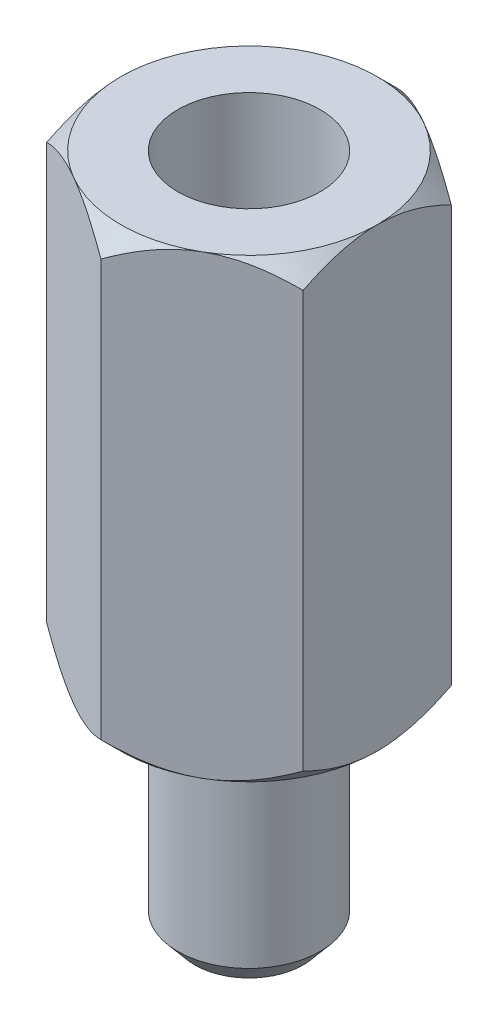
SolidWorks part; units mm, degrees
ref_plane "Front Plane" through (0, 0, 0) normal (0, 0, 1) x (1, 0, 0)
ref_plane "Top Plane" through (0, 0, 0) normal (0, 1, 0) x (1, 0, 0)
ref_plane "Right Plane" through (0, 0, 0) normal (1, 0, 0) x (0, 0, -1)
sketch "Sketch1" plane through (0, 0, 0) normal (0, 1, 0) x (1, 0, 0)
  circle A0 centre (0, 0) radius 1.25
  dimension "D1" = 2.5
extrude "Boss-Extrude1" add sketch "Sketch1" along normal blind 3.9
sketch "Sketch2" plane through (0, 3.9, 0) normal (0, 1, 0) x (1, 0, 0)
  line L1 (-2.25, -1.299) -> (0, -2.5981)
  line L2 (0, -2.5981) -> (2.25, -1.299)
  line L3 (2.25, -1.299) -> (2.25, 1.299)
  line L4 (2.25, 1.299) -> (0, 2.5981)
  line L5 (0, 2.5981) -> (-2.25, 1.299)
  line L6 (-2.25, 1.299) -> (-2.25, -1.299)
  circle A0 centre (0, 0) radius 2.25 construction
  dimension "D1" = 4.5
extrude "Boss-Extrude2" add sketch "Sketch2" along normal blind 8
sketch "Sketch3" plane through (0, 11.9, 0) normal (0, 1, 0) x (1, 0, 0)
  circle A0 centre (0, 0) radius 1.25
  dimension "D1" = 2.5
extrude "Cut-Extrude1" cut sketch "Sketch3" against normal blind 4.8
sketch "Sketch4" plane through (0, 11.9, 0) normal (0, 1, 0) x (1, 0, 0)
  circle A1 centre (0, 0) radius 2.25
extrude "Cut-Extrude2" cut sketch "Sketch4" against normal through all draft 45 flip side to cut
sketch "Sketch5" plane through (0, 3.9, 0) normal (0, -1, 0) x (1, 0, 0)
  circle A0 centre (0, 0) radius 2.25
extrude "Cut-Extrude3" cut sketch "Sketch5" against normal through all draft 45 flip side to cut
chamfer "Chamfer1" distance 0.3 angle 50 1 edges at (0, 0, 1.25)
